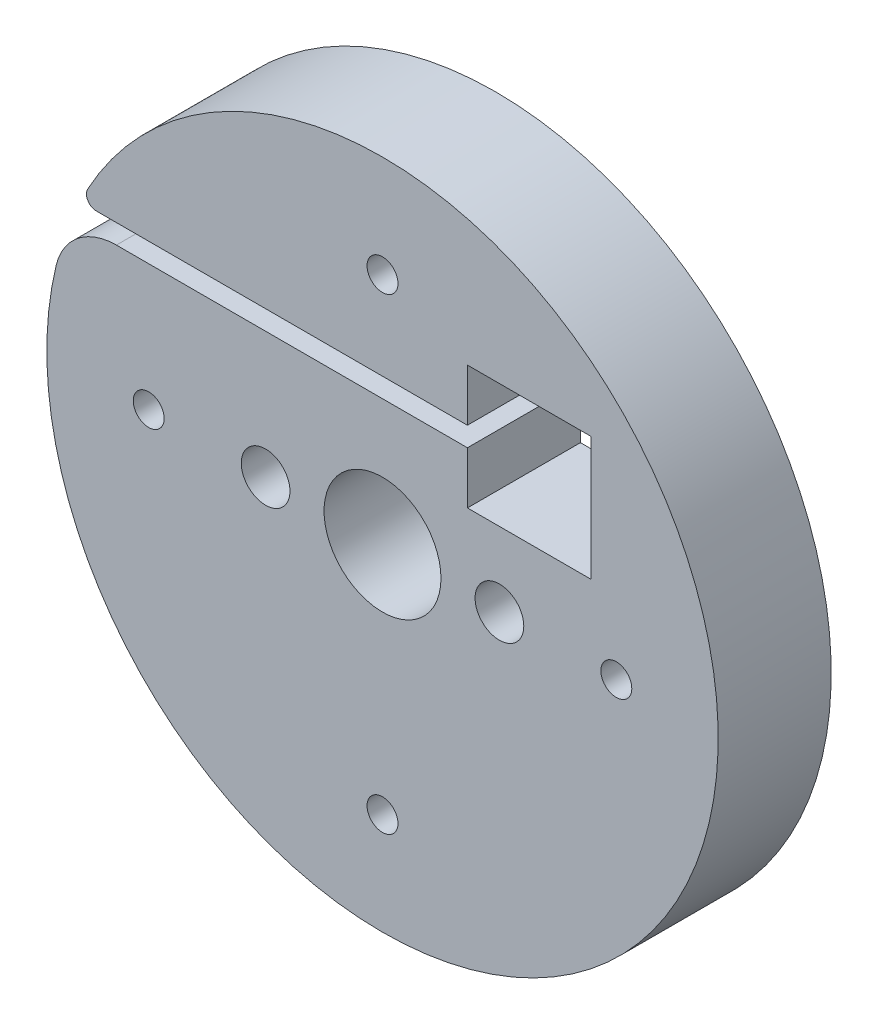
SolidWorks part; units mm, degrees
material "Balsa"
ref_plane "Front Plane" through (0, 0, 0) normal (0, 0, 1) x (1, 0, 0)
ref_plane "Top Plane" through (0, 0, 0) normal (0, 1, 0) x (1, 0, 0)
ref_plane "Right Plane" through (0, 0, 0) normal (1, 0, 0) x (0, 0, -1)
sketch "Sketch1" plane through (0, 0, 0) normal (0, 0, 1) x (1, 0, 0)
  circle A0 centre (0, 0) radius 3
  circle A1 centre (0, 0) radius 17.2292
  dimension "D1" = 6
  dimension "D2" = 34.4583
extrude "Boss-Extrude1" add sketch "Sketch1" along normal blind 5.8
sketch "Sketch2" plane through (0, 0, 5.8) normal (0, 0, 1) x (1, 0, 0)
  line L0 (0, 0) -> (0, 17.2292) construction
  circle A0 centre (0, 0) radius 17.2292 construction
  circle A1 centre (0, 12) radius 0.7937
  circle A2 centre (12, 0) radius 0.7937
  circle A3 centre (0, -12) radius 0.7937
  circle A4 centre (-12, 0) radius 0.7937
  circle A5 centre (0, 0) radius 12 construction
  dimension "D1" = 1.5875
  dimension "D2" = 12
  dimension "D3" = 4
extrude "Cut-Extrude1" cut sketch "Sketch2" against normal through all
sketch "Sketch3" plane through (0, 0, 5.8) normal (0, 0, 1) x (1, 0, 0)
  line L0 (-15.5183, 7.485) -> (4.3579, 7.485)
  line L1 (4.3579, 7.485) -> (4.3579, 10.16)
  line L2 (4.3579, 10.16) -> (10.7079, 10.16)
  line L3 (10.7079, 10.16) -> (10.7079, 3.81)
  line L4 (10.7079, 3.81) -> (4.3579, 3.81)
  line L5 (4.3579, 3.81) -> (4.3579, 6.485)
  line L6 (4.3579, 6.485) -> (-15.9621, 6.485)
  circle A0 centre (0, 0) radius 17.2292 construction
  arc A1 (-15.5183, 7.485) -> (-15.9621, 6.485) centre (0, 0) ccw
  dimension "D1" = 1
  dimension "D2" = 6.35
  dimension "D3" = 6.35
  dimension "D4" = 20.32
  dimension "D5" = 10.16
extrude "Cut-Extrude2" cut sketch "Sketch3" against normal through all
fillet "Fillet1" radius 3.175 1 edges at (-15.9621, 6.485, 2.9)
fillet "Fillet2" radius 0.508 1 edges at (-15.5183, 7.485, 2.9)
hole_wizard "M3x0.5 Tapped Hole1" positions "Sketch5" profile "Sketch4" tap size "M3x0.5" standard "Ansi Metric"
sketch "Sketch5" plane through (0, 0, 5.8) normal (0, 0, 1) x (1, 0, 0)
  line L0 (0, 0) -> (-6, 0) construction
  line L2 (0, 0) -> (6, 0) construction
  point P0 (-6, 0)
  point P1 (6, 0)
  dimension "D1" = 6
sketch "Sketch4" plane through (-6, 0, 5.8) normal (1, 0, 0) x (0, -1, 0)
  line L0 (0, 0) -> (0, 9.3871)
  line L1 (0, 9.3871) -> (1.25, 8.636)
  line L2 (1.25, 8.636) -> (1.25, 0)
  line L5 (1.25, 0) -> (0, 0)
  line L10 (0, 9.3871) -> (-1.25, 8.636) construction
  line L11 (0, -6.35) -> (0, 107.95) construction
  dimension "Tap Drill Dia." = 2.5
  dimension "Tap Drill Depth" = 8.636
  dimension "Drill Angle" = 118
